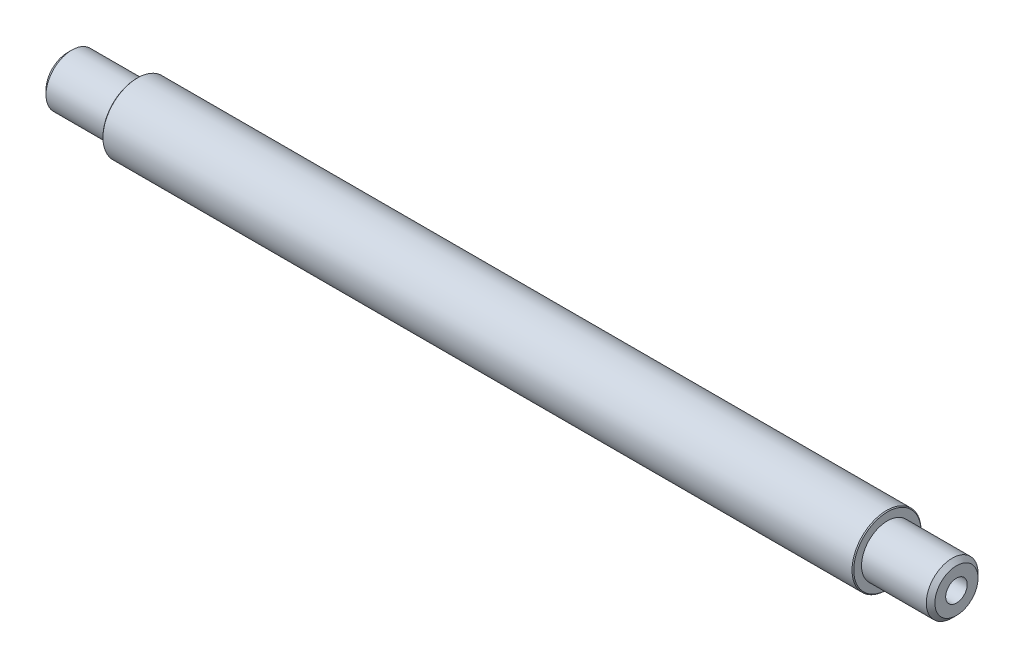
SolidWorks part; units mm, degrees
material "S45C"
ref_plane "正面" through (0, 0, 0) normal (0, 0, 1) x (1, 0, 0)
ref_plane "平面" through (0, 0, 0) normal (0, 1, 0) x (1, 0, 0)
ref_plane "右側面" through (0, 0, 0) normal (1, 0, 0) x (0, 0, -1)
sketch "ｽｹｯﾁ1" plane through (0, 0, 0) normal (0, 0, 1) x (1, 0, 0)
  line L0 (-61.2907, 0) -> (0, 0) construction
  line L1 (0, 0) -> (0, 16.1262) construction
  line L2 (43.5, 4) -> (-43.5, 4)
  line L3 (-43.5, 4) -> (-43.5, 3)
  line L4 (-43.5, 3) -> (-51.5, 3)
  line L5 (-51.5, 3) -> (-51.5, 0)
  line L6 (-51.5, 0) -> (51.5, 0)
  line L7 (51.5, 3) -> (51.5, 0)
  line L8 (43.5, 3) -> (51.5, 3)
  line L9 (43.5, 4) -> (43.5, 3)
  point P13 (0, 4)
  dimension "D1" = 87
  dimension "D2" = 8
  dimension "D3" = 6
  dimension "D4" = 103
  dimension "D5" = 8
revolve "回転1" add sketch "ｽｹｯﾁ1" angle 360 about L0
chamfer "面取り1" distance 0.5 angle 45 2 edges at (51.5, 0, 3) (-51.5, 0, 3)
chamfer "面取り2" distance 0.1 angle 45 2 edges at (43.5, 0, 4) (-43.5, 0, 4)
hole_wizard "M3 ねじ穴1" positions "ｽｹｯﾁ2" profile "ｽｹｯﾁ3" tap size "M3" standard "JIS"
sketch "ｽｹｯﾁ2" plane through (51.5, 0, 0) normal (1, 0, 0) x (0, 0, -1)
  point P0 (0, 0)
sketch "ｽｹｯﾁ3" plane through (51.5, 0, 0) normal (0, 1, 0) x (0, 0, -1)
  line L0 (0, 0) -> (0, 9.2511)
  line L1 (0, 9.2511) -> (1.25, 8.5)
  line L2 (1.25, 8.5) -> (1.25, 0)
  line L5 (1.25, 0) -> (0, 0)
  line L10 (0, 9.2511) -> (-1.25, 8.5) construction
  line L11 (0, -6.35) -> (0, 107.95) construction
  dimension "ねじ下穴ﾄﾞﾘﾙ直径" = 2.5
  dimension "ねじ下穴ﾄﾞﾘﾙの深さ" = 8.5
  dimension "ﾄﾞﾘﾙ角度" = 118
cosmetic thread "穴のねじ山1" parameters "D1"=6, "D2"=3
mirror "ﾐﾗｰ1" about plane through (0, 0, 0) normal (1, 0, 0) of "M3 ねじ穴1"
